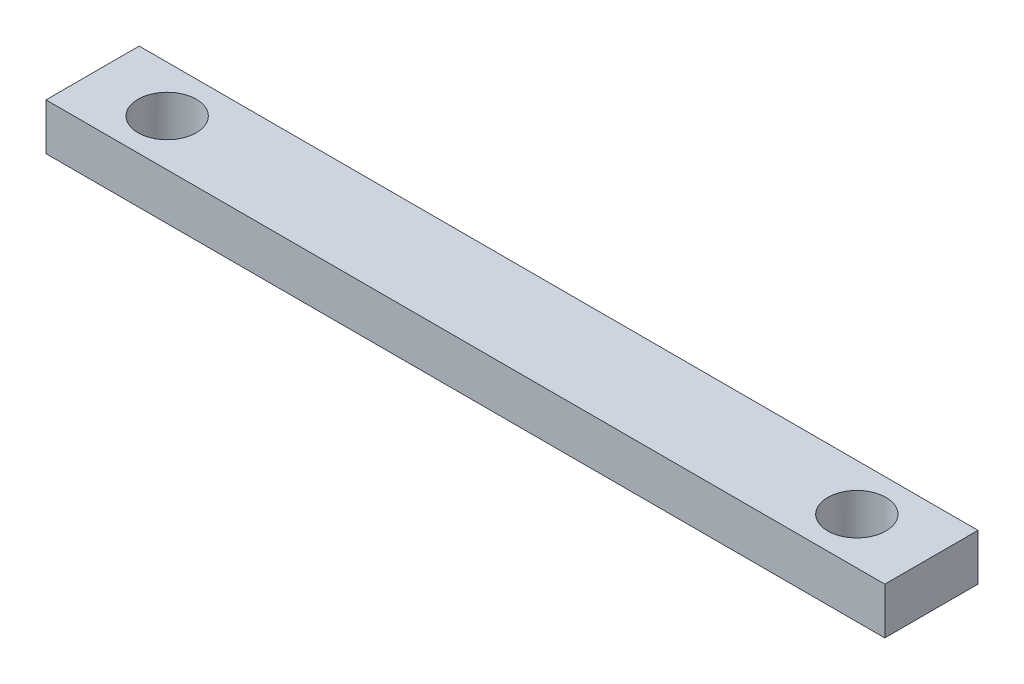
SolidWorks part; units mm, degrees
material "1060 Alloy"
ref_plane "Front Plane" through (0, 0, 0) normal (0, 0, 1) x (1, 0, 0)
ref_plane "Top Plane" through (0, 0, 0) normal (0, 1, 0) x (1, 0, 0)
ref_plane "Right Plane" through (0, 0, 0) normal (1, 0, 0) x (0, 0, -1)
sketch "Sketch1" plane through (0, 0, 0) normal (0, 1, 0) x (1, 0, 0)
  line L1 (-57.15, -6.35) -> (57.15, -6.35)
  line L2 (-57.15, -6.35) -> (-57.15, 6.35)
  line L3 (-57.15, 6.35) -> (57.15, 6.35)
  line L4 (57.15, -6.35) -> (57.15, 6.35)
  line L5 (-57.15, -6.35) -> (57.15, 6.35) construction
  line L6 (-57.15, 6.35) -> (57.15, -6.35) construction
  point P0 (0, 0)
  dimension "D1" = 114.3
  dimension "D2" = 12.7
extrude "Boss-Extrude1" add sketch "Sketch1" along normal blind 6.35
sketch "Sketch4" plane through (0, 6.35, 0) normal (0, 1, 0) x (1, 0, 0)
  line L0 (-57.15, -6.35) -> (57.15, -6.35) construction
  point P0 (-46.99, 0)
  point P2 (46.99, 0)
  dimension "D1" = 46.99
  dimension "D2" = 46.99
  dimension "D3" = 6.35
  dimension "D4" = 6.35
hole_wizard "5/16 (0.3125) Diameter Hole1" positions "Sketch4" profile "Sketch3" hole size "5/16" standard "ANSI Inch"
sketch "Sketch3" plane through (-46.99, 6.35, 0) normal (1, 0, 0) x (0, 0, 1)
  line L0 (0, 0) -> (0, 17.3707)
  line L1 (0, 17.3707) -> (3.9687, 14.986)
  line L2 (3.9687, 14.986) -> (3.9687, 0)
  line L5 (3.9687, 0) -> (0, 0)
  line L10 (0, 17.3707) -> (-3.9688, 14.986) construction
  line L11 (0, -6.35) -> (0, 107.95) construction
  dimension "Hole Dia." = 7.9375
  dimension "Hole Depth" = 14.986
  dimension "Drill Angle" = 118
